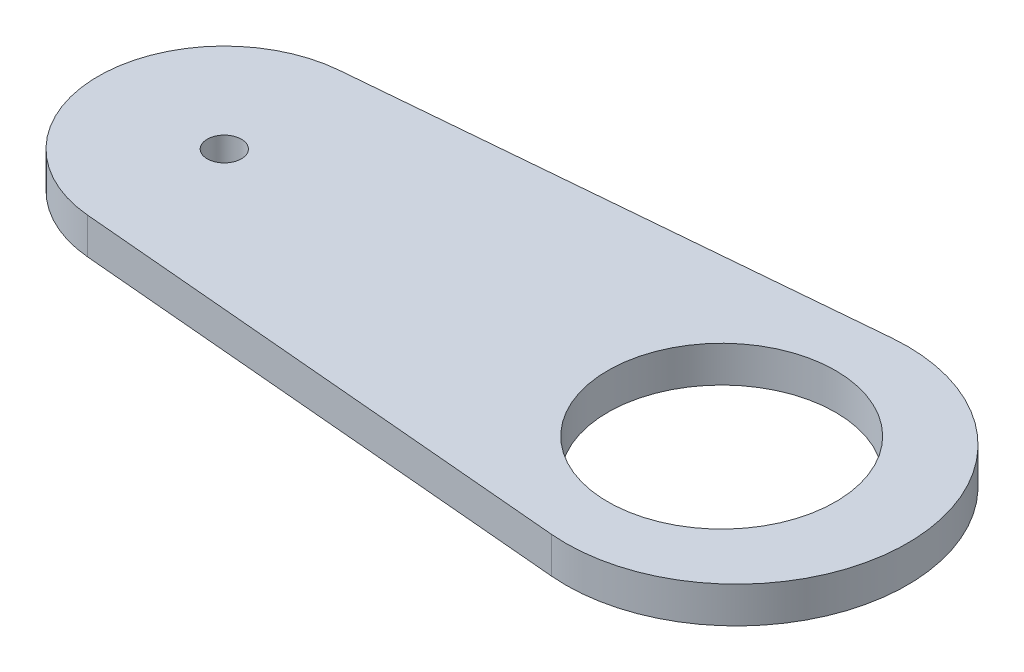
SolidWorks part; units mm, degrees
ref_plane "Front Plane" through (0, 0, 0) normal (0, 0, 1) x (1, 0, 0)
ref_plane "Top Plane" through (0, 0, 0) normal (0, 1, 0) x (1, 0, 0)
ref_plane "Right Plane" through (0, 0, 0) normal (1, 0, 0) x (0, 0, -1)
sketch "Sketch1" plane through (0, 0, 0) normal (0, 1, 0) x (1, 0, 0)
  line L0 (-36.9503, 11.0358) -> (7.7079, 14.9429)
  line L1 (-36.9503, -11.0358) -> (7.7079, -14.9429)
  line L2 (-35.9848, 0) -> (24.0152, 0) construction
  arc A1 (7.7079, 14.9429) -> (7.7079, -14.9429) centre (9.0152, 0) cw
  circle A2 centre (-35.9848, 0) radius 1.5
  circle A3 centre (9.0152, 0) radius 10
  arc A4 (-36.9503, 11.0358) -> (-36.9503, -11.0358) centre (-35.9848, 0) ccw
  dimension "D1" = 3
  dimension "D2" = 15
  dimension "D5" = 5
  dimension "D6" = 20
  dimension "D3" = 60
  dimension "D4" = 5
extrude "Boss-Extrude1" add sketch "Sketch1" along normal blind 3.18 contours L0 A1 L1 A4 | A2
sketch "Sketch2" plane through (0, 0, 0) normal (0, -1, 0) x (1, 0, 0)
  line L0 (24.0152, 0) -> (-47.0628, 0) construction
  line L1 (7.7079, -14.9429) -> (7.7079, 14.9429) construction
  line L3 (26.2389, -24.3819) -> (26.2389, -25.1797) construction
  arc A0 (7.7079, -14.9429) -> (7.7079, 14.9429) centre (9.0152, 0) ccw construction
  arc A1 (-36.9503, 11.0358) -> (-36.9503, -11.0358) centre (-35.9848, 0) ccw construction
  circle A2 centre (7.7079, 0) radius 10
  dimension "D1" = 20
extrude "Cut-Extrude1" cut sketch "Sketch2" against normal blind 3.18
sketch "Sketch3" [suppressed] plane through (0, 0, 0) normal (0, -1, 0) x (1, 0, 0)
  circle A0 centre (6.6602, 5.6249) radius 0.85 construction
  circle A1 centre (9.8597, -8.9275) radius 0.85 construction
  circle A2 centre (6.6602, 5.6249) radius 0.85
  circle A3 centre (9.8597, -8.9275) radius 0.85
extrude "Cut-Extrude2" [suppressed] cut sketch "Sketch3" against normal up to next
sketch "Sketch4" [suppressed] plane through (0, 3.18, 0) normal (0, 1, 0) x (1, 0, 0)
  circle A0 centre (8.26, 1.6513) radius 1.15
extrude "Cut-Extrude3" [suppressed] cut sketch "Sketch4" against normal up to next
